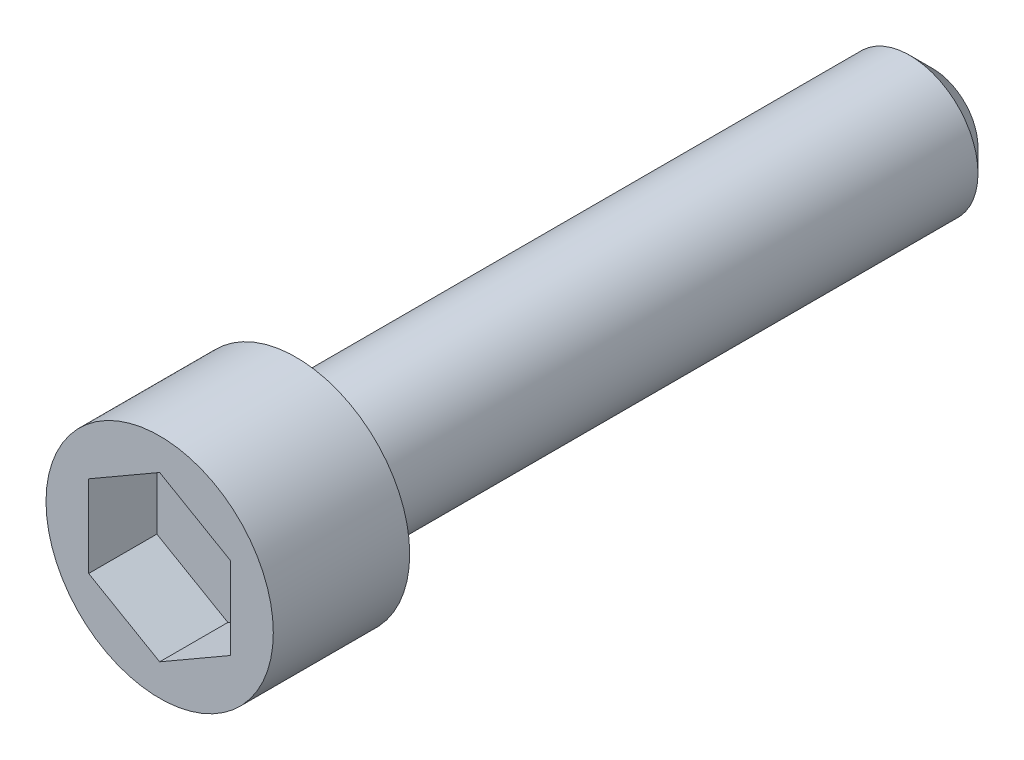
SolidWorks part; units mm, degrees
ref_plane "前视基准面" through (0, 0, 0) normal (0, 0, 1) x (1, 0, 0)
ref_plane "上视基准面" through (0, 0, 0) normal (0, 1, 0) x (1, 0, 0)
ref_plane "右视基准面" through (0, 0, 0) normal (1, 0, 0) x (0, 0, -1)
sketch "草图1" plane through (0, 0, 0) normal (0, 0, 1) x (1, 0, 0)
  circle A0 centre (0, 0) radius 1.5
extrude "凸台-拉伸1" add sketch "草图1" along normal blind 14
sketch "草图2" plane through (0, 0, 14) normal (0, 0, 1) x (1, 0, 0)
  circle A0 centre (0, 0) radius 2.5
extrude "凸台-拉伸2" add sketch "草图2" along normal blind 3
sketch "草图3" plane through (0, 0, 17) normal (0, 0, 1) x (1, 0, 0)
  line L1 (0, 1.8034) -> (-1.5618, 0.9017)
  line L2 (-1.5618, 0.9017) -> (-1.5618, -0.9017)
  line L3 (-1.5618, -0.9017) -> (0, -1.8034)
  line L4 (0, -1.8034) -> (1.5618, -0.9017)
  line L5 (1.5618, -0.9017) -> (1.5618, 0.9017)
  line L6 (1.5618, 0.9017) -> (0, 1.8034)
  circle A0 centre (0, 0) radius 1.5618 construction
extrude "切除-拉伸1" cut sketch "草图3" against normal blind 1.5
chamfer "倒角1" distance 0.5 angle 45 1 edges at (1.5, 0, 0)
